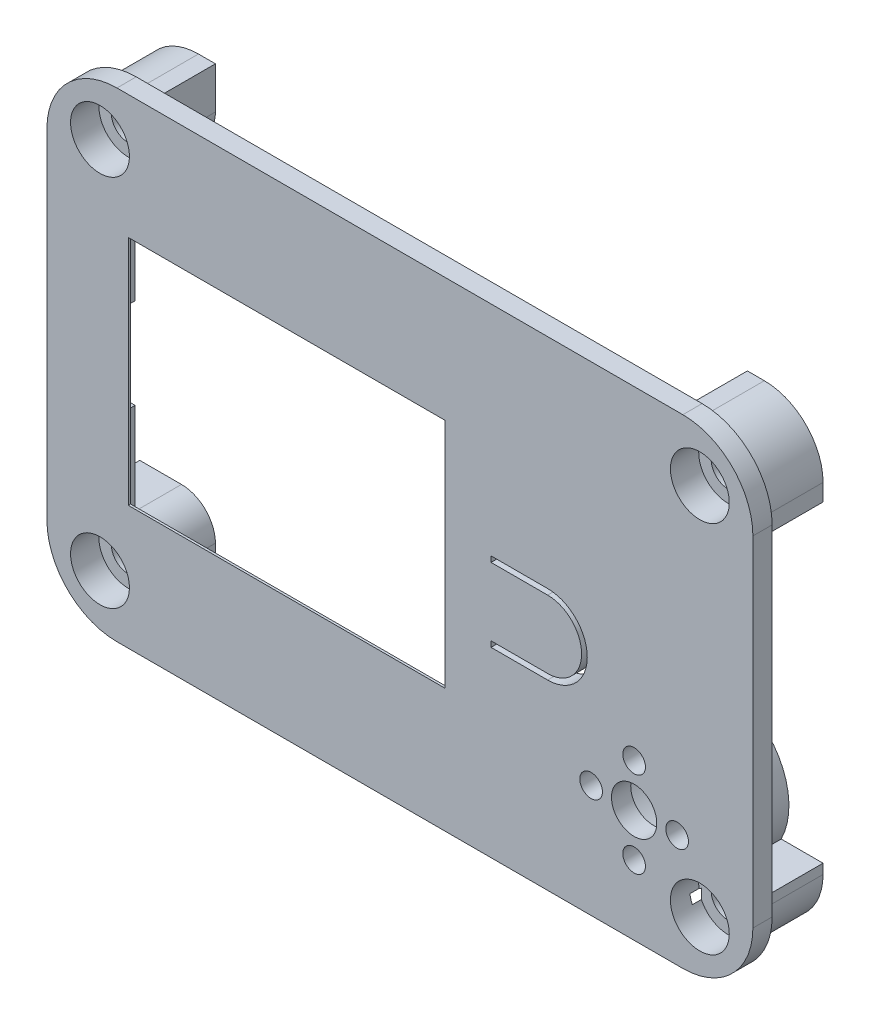
SolidWorks part; units mm, degrees
ref_plane "前视基准面" through (0, 0, 0) normal (0, 0, 1) x (1, 0, 0)
ref_plane "上视基准面" through (0, 0, 0) normal (0, 1, 0) x (1, 0, 0)
ref_plane "右视基准面" through (0, 0, 0) normal (1, 0, 0) x (0, 0, -1)
other "Configuration Table"
sketch "草图1" plane through (0, 0, 7.1) normal (0, 0, 1) x (1, 0, 0)
  line L4 (-1.1873, -2.7723) -> (-1.1873, -32.7724)
  line L5 (5, -38.9597) -> (55.0001, -38.9597)
  line L6 (61.1874, -32.7724) -> (61.1874, -2.7723)
  line L7 (55.0001, 3.415) -> (5, 3.415)
  line L8 (-1.1873, -2.7723) -> (-1.1873, -32.7724)
  line L9 (5, -38.9597) -> (55.0001, -38.9597)
  line L10 (61.1874, -32.7724) -> (61.1874, -2.7723)
  line L11 (55.0001, 3.415) -> (5, 3.415)
  arc A4 (-1.1873, -32.7724) -> (5, -38.9597) centre (5, -32.7724) ccw
  arc A5 (55.0001, -38.9597) -> (61.1874, -32.7724) centre (55.0001, -32.7724) ccw
  arc A6 (61.1874, -2.7723) -> (55.0001, 3.415) centre (55.0001, -2.7723) ccw
  arc A7 (5, 3.415) -> (-1.1873, -2.7723) centre (5, -2.7723) ccw
  arc A8 (-1.1873, -32.7724) -> (5, -38.9597) centre (5, -32.7724) ccw
  arc A9 (55.0001, -38.9597) -> (61.1874, -32.7724) centre (55.0001, -32.7724) ccw
  arc A10 (61.1874, -2.7723) -> (55.0001, 3.415) centre (55.0001, -2.7723) ccw
  arc A11 (5, 3.415) -> (-1.1873, -2.7723) centre (5, -2.7723) ccw
  circle A16 centre (56.5001, -1.2723) radius 1.5
  circle A17 centre (56.5001, -34.2724) radius 1.5
  circle A18 centre (3.5, -34.2724) radius 1.5
  circle A19 centre (3.5, -1.2724) radius 1.5
  dimension "D1" = 0
extrude "凸台-拉伸1" add sketch "草图1" along normal blind 1.5
sketch "草图5" plane through (0, 0, 7.1) normal (0, 0, -1) x (-1, 0, 0)
  line L4 (-5, 3.415) -> (-55.0001, 3.415)
  line L5 (-61.1874, -2.7723) -> (-61.1874, -32.7724)
  line L6 (-55.0001, -38.9597) -> (-5, -38.9597)
  line L7 (1.1873, -32.7724) -> (1.1873, -2.7723)
  line L8 (-5, 3.415) -> (-55.0001, 3.415) construction
  line L9 (-61.1874, -2.7723) -> (-61.1874, -32.7724) construction
  line L10 (-55.0001, -38.9597) -> (-5, -38.9597) construction
  line L11 (1.1873, -32.7724) -> (1.1873, -2.7723) construction
  line L12 (-56.5001, -31.91) -> (-60.1874, -31.91)
  line L13 (-54.1377, -34.2724) -> (-54.1377, -37.9597)
  line L14 (-53.5001, -1.2723) -> (-53.5001, 2.415)
  line L15 (-56.5001, -4.2723) -> (-60.1874, -4.2723)
  line L16 (-5, 2.415) -> (-55.0001, 2.415)
  line L17 (-60.1874, -2.7723) -> (-60.1874, -32.7724)
  line L18 (-55.0001, -37.9597) -> (-5, -37.9597)
  line L19 (0.1873, -32.7724) -> (0.1873, -2.7723)
  line L20 (-5, 2.415) -> (-55.0001, 2.415)
  line L21 (-60.1874, -2.7723) -> (-60.1874, -32.7724)
  line L22 (-55.0001, -37.9597) -> (-5, -37.9597)
  line L23 (0.1873, -32.7724) -> (0.1873, -2.7723)
  line L24 (-6.5, -1.2724) -> (-6.5, 2.415)
  line L25 (-3.5, -4.2724) -> (0.1873, -4.2724)
  line L26 (-0.0127, -17.7724) -> (12.875, -17.7724) construction
  line L27 (-0.0127, -32.7724) -> (-0.0127, -2.7723) construction
  line L28 (-3.5, -31.2724) -> (0.1873, -31.2724)
  line L29 (-6.5, -34.2724) -> (-6.5, -37.9597)
  arc A4 (1.1873, -2.7723) -> (-5, 3.415) centre (-5, -2.7723) ccw
  arc A5 (-55.0001, 3.415) -> (-61.1874, -2.7723) centre (-55.0001, -2.7723) ccw
  arc A6 (-61.1874, -32.7724) -> (-55.0001, -38.9597) centre (-55.0001, -32.7724) ccw
  arc A7 (-5, -38.9597) -> (1.1873, -32.7724) centre (-5, -32.7724) ccw
  arc A8 (1.1873, -2.7723) -> (-5, 3.415) centre (-5, -2.7723) ccw construction
  arc A9 (-55.0001, 3.415) -> (-61.1874, -2.7723) centre (-55.0001, -2.7723) ccw construction
  arc A10 (-61.1874, -32.7724) -> (-55.0001, -38.9597) centre (-55.0001, -32.7724) ccw construction
  arc A11 (-5, -38.9597) -> (1.1873, -32.7724) centre (-5, -32.7724) ccw construction
  circle A12 centre (-56.5001, -1.2723) radius 1.5
  circle A13 centre (-3.5, -1.2724) radius 1.5
  circle A14 centre (-3.5, -34.2724) radius 1.5
  circle A15 centre (-56.5001, -34.2724) radius 1.5
  arc A16 (0.1873, -2.7723) -> (-5, 2.415) centre (-5, -2.7723) ccw
  arc A17 (-55.0001, 2.415) -> (-60.1874, -2.7723) centre (-55.0001, -2.7723) ccw
  arc A18 (-60.1874, -32.7724) -> (-55.0001, -37.9597) centre (-55.0001, -32.7724) ccw
  arc A19 (-5, -37.9597) -> (0.1873, -32.7724) centre (-5, -32.7724) ccw
  arc A20 (0.1873, -2.7723) -> (-5, 2.415) centre (-5, -2.7723) ccw
  arc A21 (-55.0001, 2.415) -> (-60.1874, -2.7723) centre (-55.0001, -2.7723) ccw
  arc A22 (-60.1874, -32.7724) -> (-55.0001, -37.9597) centre (-55.0001, -32.7724) ccw
  arc A23 (-5, -37.9597) -> (0.1873, -32.7724) centre (-5, -32.7724) ccw
  arc A24 (-54.1377, -34.2724) -> (-56.5001, -31.91) centre (-56.5001, -34.2724) ccw
  arc A25 (-56.5001, -4.2723) -> (-53.5001, -1.2723) centre (-56.5001, -1.2723) ccw
  arc A26 (-6.5, -1.2724) -> (-3.5, -4.2724) centre (-3.5, -1.2724) ccw
  arc A27 (-6.5, -34.2724) -> (-3.5, -31.2724) centre (-3.5, -34.2724) cw
  dimension "D3" = 6
  dimension "D4" = 6
  dimension "D1" = 0
  dimension "D2" = 1
sketch "草图2" plane through (0, 0, 7.1) normal (0, 0, -1) x (-1, 0, 0)
  line L0 (-50.6932, -28.2599) -> (-50.6932, -29.7599) construction
  circle A0 centre (-50.6932, -29.0099) radius 5.4794
  arc A1 (-55.0856, -33.7733) -> (-55.8646, -32.9137) centre (-50.6932, -29.0099) ccw
  arc A3 (-55.0856, -33.7733) -> (-55.8646, -32.9137) centre (-56.5001, -34.2724) ccw
  circle A5 centre (-50.6932, -29.0099) radius 6.4794 construction
  point P7 (-44.2137, -29.0099)
  dimension "D1" = 1
extrude "凸台-拉伸2" add sketch "草图2" along normal up to surface (5.4999 mm away)
sketch "草图3" plane through (0, 0, 7.1) normal (0, 0, -1) x (-1, 0, 0)
  line L0 (-50.6932, -29.0099) -> (-56.1726, -29.0099) construction
  circle A0 centre (-50.6932, -29.0099) radius 2
  circle A1 centre (-50.6932, -29.0099) radius 5.4794 construction
  circle A2 centre (-54.4932, -29.0099) radius 1
  circle A3 centre (-50.6932, -25.2099) radius 1
  circle A4 centre (-46.8932, -29.0099) radius 1
  circle A5 centre (-50.6932, -32.8099) radius 1
  dimension "D1" = 4
  dimension "D2" = 2
  dimension "D3" = 3.8
  dimension "D4" = 4
extrude "切除-拉伸1" cut sketch "草图3" against normal up to surface (1.5 mm away) up to face at (5, -34.2724, 8.6)
sketch "草图4" plane through (0, 0, 8.6) normal (0, 0, 1) x (1, 0, 0)
  line L9 (34, -28.0224) -> (6, -28.0224)
  line L10 (34, -28.0224) -> (34, -7.5224)
  line L11 (34, -7.5224) -> (6, -7.5224)
  line L12 (6, -28.0224) -> (6, -7.5224)
  line L13 (34, -28.0224) -> (6, -7.5224) construction
  line L14 (34, -7.5224) -> (6, -28.0224) construction
  point P6 (20, -17.7724)
  dimension "D1" = 28
  dimension "D2" = 20.5
extrude "切除-拉伸2" cut sketch "草图4" against normal up to surface (1.5 mm away) contours L12 L9 L10 L11 up to face at (51.7518, -29.9693, 7.1)
extrude "凸台-拉伸3" add sketch "草图5" along normal up to surface (5.4999 mm away) contours L15 A25 L14 L20 A21 L21 A12 | L13 A24 L12 L21 A22 L22 A15 | A27 L29 L22 A23 L23 L28 A14 | L24 A26 L25 L23 A20 L20 A13
sketch "草图7" plane through (0, 0, 8.6) normal (0, 0, 1) x (1, 0, 0)
  line L1 (4.9, -6.4224) -> (35.1, -6.4224)
  line L2 (4.9, -6.4224) -> (4.9, -29.1224)
  line L3 (4.9, -29.1224) -> (35.1, -29.1224)
  line L4 (35.1, -6.4224) -> (35.1, -29.1224)
  line L5 (4.9, -6.4224) -> (35.1, -29.1224) construction
  line L6 (4.9, -29.1224) -> (35.1, -6.4224) construction
  point P0 (20, -17.7724)
  dimension "D1" = 30.2
  dimension "D2" = 22.7
extrude "切除-拉伸3" cut sketch "草图7" against normal up to surface (1.5 mm away) up to face at (3.4454, -1.2177, 7.1)
sketch "草图8" plane through (0, 0, 7.1) normal (0, 0, -1) x (-1, 0, 0)
  circle A1 centre (-43.0531, -19.3624) radius 1.5177
extrude "凸台-拉伸5" add sketch "草图8" along normal up to surface (0.5249 mm away) contours A1
sketch "草图10" plane through (0, 0, 7.1) normal (0, 0, -1) x (-1, 0, 0)
  line L0 (-35.1, -6.4224) -> (-4.9, -29.1224) construction
  line L9 (-4.9, -6.4224) -> (-35.1, -29.1224) construction
  line L11 (-35.1, -3.8724) -> (-4.9, -3.8724)
  line L12 (-35.1, -3.8724) -> (-35.1, -31.6724)
  line L13 (-35.1, -31.6724) -> (-4.9, -31.6724)
  line L14 (-4.9, -3.8724) -> (-4.9, -31.6724)
  line L15 (-35.1, -3.8724) -> (-4.9, -31.6724) construction
  line L16 (-35.1, -31.6724) -> (-4.9, -3.8724) construction
  point P4 (-20, -17.7724)
  dimension "D1" = 27.8
  dimension "D2" = 30.2
extrude "切除-拉伸5" cut sketch "草图10" against normal blind 1.1 contours L12 L11 L14 L13
sketch "草图6" plane through (0, 0, 8.6) normal (0, 0, 1) x (1, 0, 0)
  line L4 (-1.1873, -2.7723) -> (-1.1873, -32.7724)
  line L5 (5, -38.9597) -> (55.0001, -38.9597)
  line L6 (61.1874, -32.7724) -> (61.1874, -2.7723)
  line L7 (55.0001, 3.415) -> (5, 3.415)
  line L8 (-1.1873, -2.7723) -> (-1.1873, -32.7724)
  line L9 (5, -38.9597) -> (55.0001, -38.9597)
  line L10 (61.1874, -32.7724) -> (61.1874, -2.7723)
  line L11 (55.0001, 3.415) -> (5, 3.415)
  line L12 (6, -28.0224) -> (6, -7.5224)
  line L13 (34, -7.5224) -> (6, -7.5224)
  line L14 (34, -28.0224) -> (6, -28.0224)
  line L15 (34, -28.0224) -> (34, -7.5224)
  circle A0 centre (50.6932, -25.2099) radius 1 construction
  circle A1 centre (50.6932, -29.0099) radius 2 construction
  circle A2 centre (54.4932, -29.0099) radius 1 construction
  circle A3 centre (50.6932, -32.8099) radius 1 construction
  arc A4 (5, 3.415) -> (-1.1873, -2.7723) centre (5, -2.7723) ccw
  arc A5 (-1.1873, -32.7724) -> (5, -38.9597) centre (5, -32.7724) ccw
  arc A6 (55.0001, -38.9597) -> (61.1874, -32.7724) centre (55.0001, -32.7724) ccw
  arc A7 (61.1874, -2.7723) -> (55.0001, 3.415) centre (55.0001, -2.7723) ccw
  arc A8 (5, 3.415) -> (-1.1873, -2.7723) centre (5, -2.7723) ccw
  arc A9 (-1.1873, -32.7724) -> (5, -38.9597) centre (5, -32.7724) ccw
  arc A10 (55.0001, -38.9597) -> (61.1874, -32.7724) centre (55.0001, -32.7724) ccw
  arc A11 (61.1874, -2.7723) -> (55.0001, 3.415) centre (55.0001, -2.7723) ccw
  circle A12 centre (46.8932, -29.0099) radius 1 construction
  circle A13 centre (46.8932, -29.0099) radius 1
  circle A14 centre (50.6932, -32.8099) radius 1
  circle A15 centre (54.4932, -29.0099) radius 1
  circle A16 centre (50.6932, -29.0099) radius 2
  circle A17 centre (50.6932, -25.2099) radius 1
  dimension "D1" = 0
extrude "凸台-拉伸4" add sketch "草图6" along normal blind 0.2
sketch "草图9" plane through (0, 0, 7.1) normal (0, 0, -1) x (-1, 0, 0)
  line L0 (-43.0531, -16.3624) -> (-38.0531, -16.3624)
  line L1 (-38.0531, -15.8624) -> (-38.0531, -16.3624)
  line L2 (-43.0531, -22.3624) -> (-38.0531, -22.3624)
  line L3 (-43.0531, -22.8624) -> (-38.0531, -22.8624)
  line L4 (-43.0531, -15.8624) -> (-38.0531, -15.8624)
  line L5 (-38.0531, -22.3624) -> (-38.0531, -22.8624)
  arc A0 (-43.0531, -16.3624) -> (-43.0531, -22.3624) centre (-43.0531, -19.3624) ccw
  arc A1 (-43.0531, -15.8624) -> (-43.0531, -22.8624) centre (-43.0531, -19.3624) ccw
  dimension "D1" = 6
  dimension "D2" = 5
  dimension "D3" = 5
  dimension "D4" = 0.5
extrude "切除-拉伸4" cut sketch "草图9" against normal blind 14.2
sketch "草图13" plane through (0, 0, 7.1) normal (0, 0, -1) x (-1, 0, 0)
  line L0 (-43.0531, -16.3624) -> (-38.0531, -16.3624) construction
  line L1 (-43.0531, -16.3624) -> (-38.0531, -16.3624)
  line L2 (-38.0531, -22.3624) -> (-43.0531, -22.3624) construction
  line L3 (-38.0531, -22.3624) -> (-43.0531, -22.3624)
  line L4 (-38.0531, -16.3624) -> (-37.2531, -16.3624)
  line L5 (-37.2531, -16.3624) -> (-37.2531, -22.3624)
  line L6 (-37.2531, -22.3624) -> (-38.0531, -22.3624)
  arc A0 (-43.0531, -16.3624) -> (-43.0531, -22.3624) centre (-43.0531, -19.3624) ccw construction
  circle A1 centre (-43.0531, -19.3624) radius 1.5177
  circle A2 centre (-43.0531, -19.3624) radius 1.5177
  arc A3 (-43.0531, -16.3624) -> (-43.0531, -22.3624) centre (-43.0531, -19.3624) ccw
  dimension "D2" = 0.8
  dimension "D1" = 0
extrude "切除-拉伸8" cut sketch "草图13" against normal blind 0.7
sketch "草图11" plane through (0, 0, 7.1) normal (0, 0, -1) x (-1, 0, 0)
  circle A0 centre (-56.5001, -1.2723) radius 1.5
  circle A1 centre (-3.5, -1.2724) radius 1.5
  circle A2 centre (-56.5001, -34.2724) radius 1.5 construction
  circle A3 centre (-3.5, -34.2724) radius 1.5 construction
  circle A4 centre (-56.5001, -34.2724) radius 1.5
  circle A5 centre (-3.5, -34.2724) radius 1.5
extrude "切除-拉伸6" cut sketch "草图11" against normal up to surface (1.7 mm away) up to face at (41.3656, -19.3624, 8.8)
sketch "草图12" plane through (0, 0, 8.8) normal (0, 0, 1) x (1, 0, 0)
  line L0 (-1.1873, -17.7724) -> (62.8912, -17.7724) construction
  line L1 (-1.1873, -2.7723) -> (-1.1873, -32.7724) construction
  line L2 (30.0001, 3.415) -> (30.0001, -39.5074) construction
  line L3 (55.0001, 3.415) -> (5, 3.415) construction
  circle A0 centre (3.5, -1.2724) radius 2.6
  circle A1 centre (56.5001, -1.2724) radius 2.6
  circle A2 centre (56.5001, -34.2724) radius 2.6
  circle A3 centre (3.5, -34.2724) radius 2.6
  dimension "D1" = 5.2
extrude "切除-拉伸7" cut sketch "草图12" against normal blind 2.5
sketch "草图14" plane through (0, 0, 7.1) normal (0, 0, -1) x (-1, 0, 0)
  line L0 (-4.9, -31.6191) -> (-4.9, -3.9257) construction
  line L1 (-5.7, -21.7724) -> (-4.1, -21.7724)
  line L2 (-5.7, -21.7724) -> (-5.7, -13.7724)
  line L3 (-5.7, -13.7724) -> (-4.1, -13.7724)
  line L4 (-4.1, -21.7724) -> (-4.1, -13.7724)
  line L5 (-5.7, -21.7724) -> (-4.1, -13.7724) construction
  line L6 (-5.7, -13.7724) -> (-4.1, -21.7724) construction
  line L7 (-4.9, -6.4224) -> (-4.9, -29.1224) construction
  point P0 (-4.9, -17.7724)
  dimension "D1" = 8
  dimension "D2" = 0.8
extrude "切除-拉伸9" cut sketch "草图14" against normal up to surface (1.5 mm away) up to face at (20, -17.7724, 8.6)
